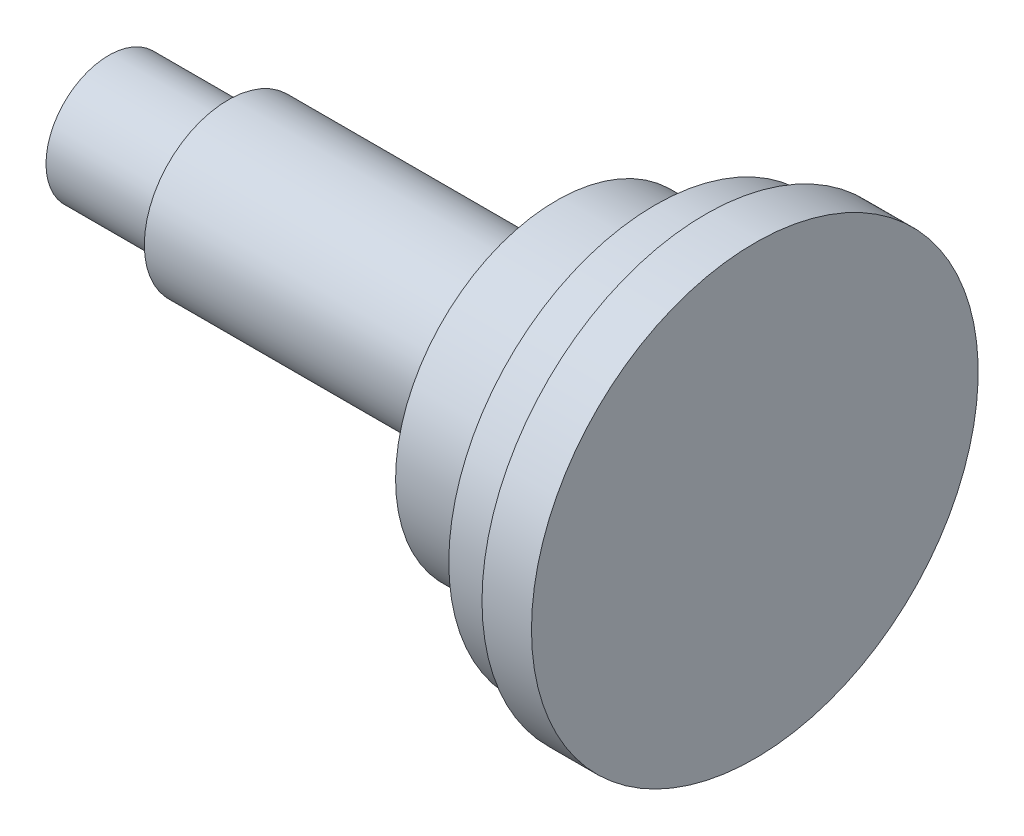
SolidWorks part; units mm, degrees
ref_plane "Front Plane" through (0, 0, 0) normal (0, 0, 1) x (1, 0, 0)
ref_plane "Top Plane" through (0, 0, 0) normal (0, 1, 0) x (1, 0, 0)
ref_plane "Right Plane" through (0, 0, 0) normal (1, 0, 0) x (0, 0, -1)
sketch "Sketch1" plane through (0, 0, 0) normal (0, 0, 1) x (1, 0, 0)
  line L0 (-68.8831, 0) -> (68.8831, 0) construction
  line L1 (-64.511, 0) -> (-64.511, 9.55)
  line L2 (-64.511, 9.55) -> (-46.3457, 9.55)
  line L3 (-46.3457, 9.55) -> (-46.3457, 12.75)
  line L4 (-46.3457, 12.75) -> (3.6543, 12.75)
  line L5 (3.6543, 12.75) -> (3.6543, 24.5)
  line L6 (3.6543, 24.5) -> (18.6543, 24.5)
  line L7 (18.6543, 24.5) -> (18.6543, 31.4)
  line L8 (18.6543, 31.4) -> (26.3096, 31.4)
  line L9 (26.3096, 31.4) -> (26.3096, 34)
  line L10 (26.3096, 34) -> (33.8407, 34)
  line L11 (33.8407, 34) -> (33.8407, 0)
  line L12 (-64.511, 0) -> (33.8407, 0)
  point P4 (0, 0)
  dimension "D1" = 12.75
  dimension "D2" = 9.55
  dimension "D3" = 50
  dimension "D4" = 15
  dimension "D5" = 24.5
  dimension "D6" = 31.4
  dimension "D7" = 34
revolve "Revolve1" add sketch "Sketch1" angle 360 about L12
sketch "Sketch2" plane through (0, 0, 0) normal (0, 0, 1) x (1, 0, 0)
  line L0 (-64.511, 0) -> (75.489, 0) construction
  line L1 (-64.511, 9.55) -> (-64.511, -9.55) construction
  dimension "D1" = 140
